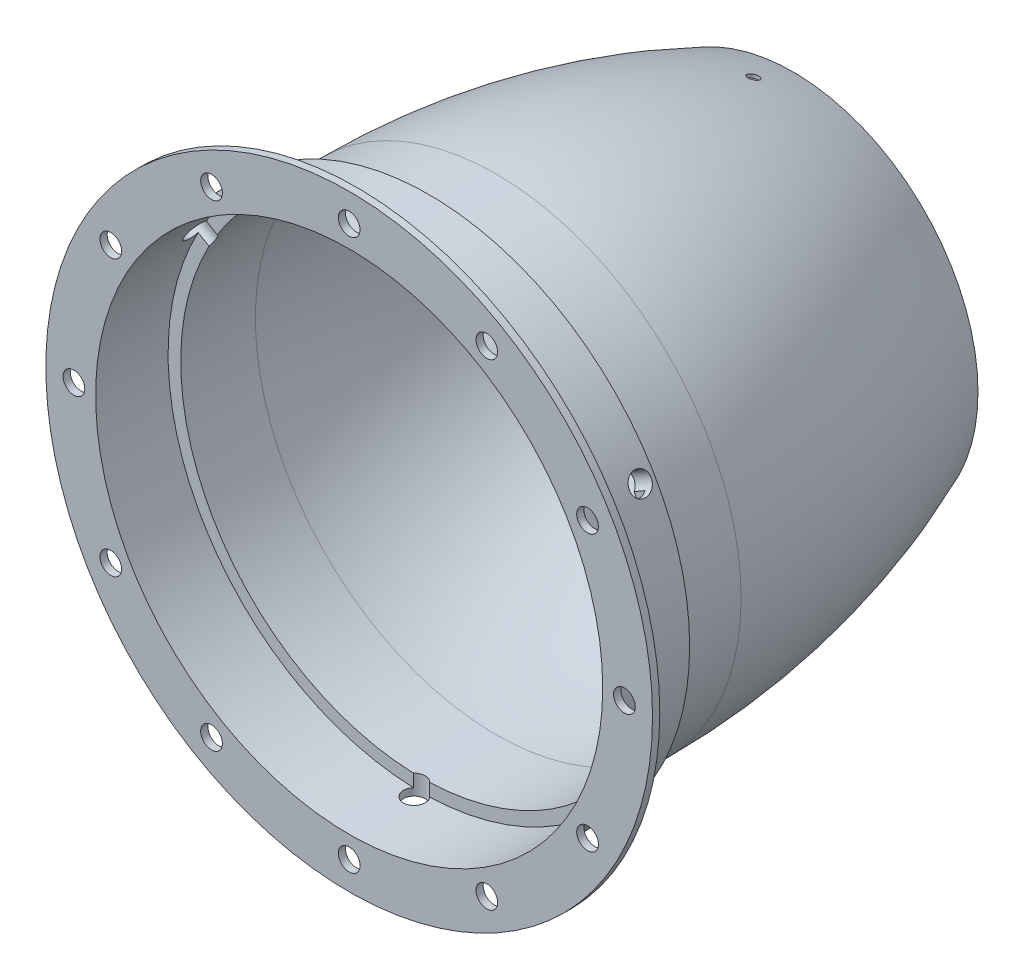
SolidWorks part; units mm, degrees
ref_plane "Plan1" through (0, 0, 0) normal (0, 0, 1) x (1, 0, 0)
ref_plane "Plan2" through (0, 0, 0) normal (0, 1, 0) x (1, 0, 0)
ref_plane "Plan3" through (0, 0, 0) normal (1, 0, 0) x (0, 0, -1)
sketch "Esquisse1" plane through (0, 0, 0) normal (1, 0, 0) x (0, 0, -1)
  line L0 (-48.0086, 0) -> (100.4573, 0) construction
  line L1 (0, 41.875) -> (0, 35)
  line L2 (0, 35) -> (10, 35)
  line L3 (10, 35) -> (10, 33.25)
  line L4 (10, 33.25) -> (20.3, 33.25)
  line L5 (0, 41.875) -> (1, 41.875)
  line L6 (1, 41.875) -> (1, 36)
  line L7 (1, 36) -> (11, 36)
  line L8 (11, 36) -> (11, 33.8)
  line L9 (11, 33.8) -> (20.3, 33.8)
  line L10 (61.3, 25.5) -> (61.3, 25)
  arc A0 (20.3, 33.25) -> (61.3, 25) centre (20.3, -72.7538) cw
  arc A1 (20.3, 33.8) -> (61.3, 25.5) centre (20.3, -71.6151) cw
  point P13 (61.3, 25)
  point P16 (61.3, 25.5)
  dimension "D1" = 1
  dimension "D2" = 83.75
  dimension "D3" = 70
  dimension "D4" = 72
  dimension "D5" = 10
  dimension "D6" = 10
  dimension "D7" = 66.5
  dimension "D8" = 67.6
  dimension "D9" = 9.3
  dimension "D10" = 50
  dimension "D11" = 61.3
  dimension "D12" = 0.55
  dimension "D13" = 51
revolve "Base-Révolution" add sketch "Esquisse1" angle 360 about L0
sketch "Esquisse2" plane through (0, 0, 0) normal (0, 0, 1) x (1, 0, 0)
  line L0 (0, 0) -> (0, -37.995) construction
  line L1 (0, 0) -> (0, 38) construction
  circle A0 centre (0, -37.995) radius 1.5
  circle A1 centre (0, 38) radius 1.5
  circle A2 centre (-18.9975, -32.9046) radius 1.5
  circle A3 centre (-32.9046, -18.9975) radius 1.5 [skipped]
  circle A4 centre (-37.995, 0) radius 1.5
  circle A5 centre (-32.9046, 18.9975) radius 1.5
  circle A6 centre (-18.9975, 32.9046) radius 1.5
  circle A7 centre (0, 37.995) radius 1.5 [skipped]
  circle A8 centre (18.9975, 32.9046) radius 1.5
  circle A9 centre (32.9046, 18.9975) radius 1.5
  circle A10 centre (37.995, 0) radius 1.5
  circle A11 centre (32.9046, -18.9975) radius 1.5 [skipped]
  circle A12 centre (18.9975, -32.9046) radius 1.5
  circle A13 centre (32.909, -19) radius 1.5
  circle A14 centre (-32.909, -19) radius 1.5
  dimension "D1" = 3
  dimension "D2" = 37.995
  dimension "D3" = 37.995
  dimension "D4" = 3
  dimension "D5" = 38
  dimension "D6" = 38
  dimension "D7" = 12
extrude "Enlèv. mat.-Extru.1" cut sketch "Esquisse2" against normal through all
sketch "Esquisse4" plane through (0, 0, 0) normal (0, 1, 0) x (1, 0, 0)
  line L0 (0, 1) -> (0, 0) construction
  circle A0 centre (0, 9) radius 1.5
  dimension "D1" = 3
  dimension "D2" = 9
extrude "Enlèv. mat.-Extru.2" cut sketch "Esquisse4" against normal through all
pattern_circular "Répétition circulaire1" count 3 over 360 about axis through (0, 0, 48.0086) along (0, 0, -1) of "Enlèv. mat.-Extru.2"
sketch "Esquisse5" plane through (0, 0, 0) normal (0, 1, 0) x (0, 0, -1)
  line L0 (61.3, -25.5) -> (61.3, 25.5) construction
  line L1 (51.9928, 0) -> (62.8325, 0) construction
  line L2 (-48.0086, 0) -> (100.4573, 0) construction
  circle A0 centre (55.8, 0) radius 0.75
  dimension "D1" = 1.5
  dimension "D2" = 5.5
extrude "Enlèv. mat.-Extru.3" cut sketch "Esquisse5" along normal through all
